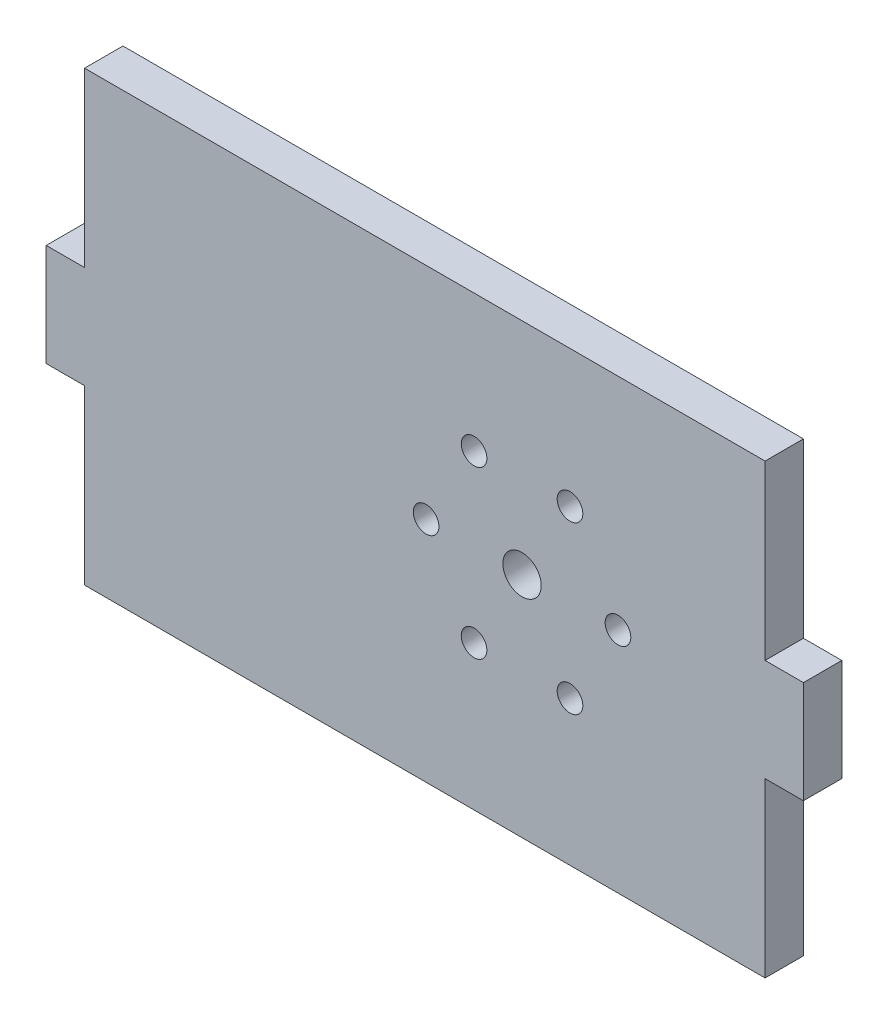
SolidWorks part; units mm, degrees
ref_plane "Alzado" through (0, 0, 0) normal (0, 0, 1) x (1, 0, 0)
ref_plane "Planta" through (0, 0, 0) normal (0, 1, 0) x (1, 0, 0)
ref_plane "Vista lateral" through (0, 0, 0) normal (1, 0, 0) x (0, 0, -1)
sketch "Croquis1" plane through (0, 0, 0) normal (0, 0, 1) x (1, 0, 0)
  line L0 (29.6, -12.5) -> (26.6, -12.5)
  line L1 (-29.6, -17.5) -> (29.6, -17.5)
  line L2 (-29.6, 2.5) -> (-29.6, 7.5)
  line L3 (-29.6, 17.5) -> (29.6, 17.5)
  line L4 (29.6, -17.5) -> (29.6, 17.5) construction
  line L5 (-29.6, -17.5) -> (29.6, 17.5) construction
  line L6 (-29.6, 17.5) -> (29.6, -17.5) construction
  line L7 (26.6, -12.5) -> (26.6, -7.5)
  line L8 (26.6, -7.5) -> (29.6, -7.5)
  line L9 (29.6, -7.5) -> (29.6, -2.5)
  line L10 (29.6, -2.5) -> (26.6, -2.5)
  line L11 (26.6, -2.5) -> (26.6, 2.5)
  line L12 (26.6, 2.5) -> (29.6, 2.5)
  line L13 (29.6, 2.5) -> (29.6, 7.5)
  line L14 (29.6, 7.5) -> (26.6, 7.5)
  line L15 (26.6, 7.5) -> (26.6, 12.5)
  line L16 (26.6, 12.5) -> (29.6, 12.5)
  line L17 (29.6, 12.5) -> (29.6, 17.5)
  line L18 (29.6, -17.5) -> (29.6, -12.5)
  line L19 (26.6, -17.5) -> (26.6, 17.5) construction
  line L20 (0, -17.5) -> (0, 17.5) construction
  line L21 (-29.6, 12.5) -> (-29.6, 17.5)
  line L22 (-26.6, 12.5) -> (-29.6, 12.5)
  line L23 (-26.6, 7.5) -> (-26.6, 12.5)
  line L24 (-29.6, 7.5) -> (-26.6, 7.5)
  line L25 (-26.6, -17.5) -> (-26.6, 17.5) construction
  line L26 (-26.6, 2.5) -> (-29.6, 2.5)
  line L27 (-26.6, -2.5) -> (-26.6, 2.5)
  line L28 (-29.6, -2.5) -> (-26.6, -2.5)
  line L29 (-26.6, -7.5) -> (-29.6, -7.5)
  line L30 (-29.6, -12.5) -> (-26.6, -12.5)
  line L31 (-26.6, -12.5) -> (-26.6, -7.5)
  line L32 (-29.6, -17.5) -> (-29.6, 17.5) construction
  line L33 (-29.6, -17.5) -> (-29.6, -12.5)
  line L34 (-29.6, -7.5) -> (-29.6, -2.5)
  point P0 (0, 0)
  point P8 (28.1, -12.5)
  point P19 (28.1, -2.5)
  point P20 (28.1, 2.5)
  point P21 (28.1, 7.5)
  dimension "D1" = 59.2
  dimension "D2" = 35
  dimension "D3" = 5
  dimension "D4" = 5
  dimension "D5" = 5
  dimension "D6" = 5
  dimension "D7" = 5
  dimension "D8" = 5
  dimension "D9" = 3
extrude "Saliente-Extruir1" add sketch "Croquis1" along normal blind 3 contours L3 L17 L16 L15 L14 L13 L12 L11 L10 L9 L8 L7 L0 L18 L1 L33 L30 L31 L29 L34 L28 L27 L26 L2 L24 L23 L22 L21
sketch "Croquis2" plane through (0, 0, 0) normal (0, 0, -1) x (-1, 0, 0)
  line L0 (-26.6, 0.31) -> (26.6, 0.31) construction
  line L3 (29.6, -17.5) -> (-29.6, -17.5) construction
  line L4 (-26.6, -2.5) -> (-26.6, 2.5) construction
  circle A0 centre (-7.6, 0.31) radius 1.5
  circle A1 centre (-15.1, 0.31) radius 1.0026
  circle A2 centre (-11.35, 6.8052) radius 1.0026
  circle A3 centre (-3.85, 6.8052) radius 1.0026
  circle A4 centre (-0.1, 0.31) radius 1.0026
  circle A5 centre (-3.85, -6.1852) radius 1.0026
  circle A6 centre (-11.35, -6.1852) radius 1.0026
  point P2 (0, 0)
  point P23 (0, 0)
  point P24 (-7.6, 0.31)
  dimension "D1" = 7.5
  dimension "D2" = 3
  dimension "D3" = 2.0052
  dimension "D5" = 17.81
  dimension "D6" = 19
  dimension "D4" = 6
extrude "Cortar-Extruir1" cut sketch "Croquis2" against normal up to next
sketch "Croquis3" plane through (0, 0, 3) normal (0, 0, 1) x (1, 0, 0)
  line L0 (-29.6, -17.5) -> (29.6, -17.5) construction
  line L1 (-26.6, -17.5) -> (-29.6, -17.5)
  line L2 (-26.6, -17.5) -> (-26.6, 17.5)
  line L3 (-26.6, 17.5) -> (-29.6, 17.5)
  line L4 (-29.6, -17.5) -> (-29.6, 17.5)
  line L5 (-29.6, 17.5) -> (29.6, 17.5) construction
  line L6 (29.6, -17.5) -> (26.6, -17.5)
  line L7 (29.6, -17.5) -> (29.6, 17.5)
  line L8 (29.6, 17.5) -> (26.6, 17.5)
  line L9 (26.6, -17.5) -> (26.6, 17.5)
  dimension "D1" = 3
  dimension "D2" = 3
extrude "Cortar-Extruir2" cut sketch "Croquis3" against normal up to next
sketch "Croquis4" plane through (0, 0, 3) normal (0, 0, 1) x (1, 0, 0)
  line L0 (26.6, -17.5) -> (26.6, 17.5) construction
  line L1 (26.6, -4) -> (29.6, -4)
  line L2 (26.6, -4) -> (26.6, 4)
  line L3 (26.6, 4) -> (29.6, 4)
  line L4 (29.6, -4) -> (29.6, 4)
  line L5 (-26.6, -17.5) -> (-26.6, 17.5) construction
  line L6 (-26.6, 4) -> (-29.6, 4)
  line L7 (-26.6, 4) -> (-26.6, -4)
  line L8 (-26.6, -4) -> (-29.6, -4)
  line L9 (-29.6, 4) -> (-29.6, -4)
  line L10 (-26.6, 0) -> (26.6, 0) construction
  dimension "D1" = 8
  dimension "D2" = 3
extrude "Saliente-Extruir2" add sketch "Croquis4" against normal blind 3
